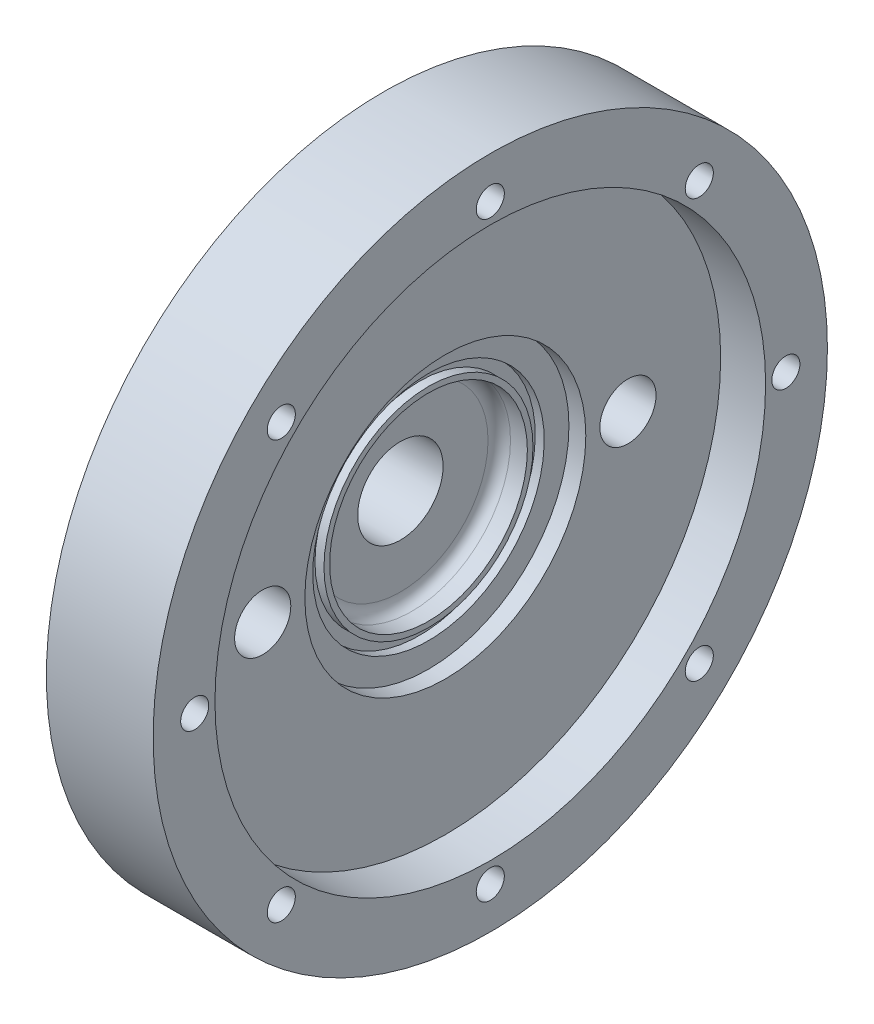
SolidWorks part; units mm, degrees
ref_plane "Front Plane" through (0, 0, 0) normal (0, 0, 1) x (1, 0, 0)
ref_plane "Top Plane" through (0, 0, 0) normal (0, 1, 0) x (1, 0, 0)
ref_plane "Right Plane" through (0, 0, 0) normal (1, 0, 0) x (0, 0, -1)
sketch "Sketch1" plane through (0, 0, 0) normal (0, 0, 1) x (1, 0, 0)
  line L1 (0, 76.2) -> (-10.16, 76.2)
  line L2 (-10.16, 76.2) -> (-10.16, 21.082)
  line L3 (-15.24, 16.002) -> (-31.75, 16.002)
  line L4 (-31.75, 16.002) -> (-31.75, 9.652)
  line L5 (-31.75, 9.652) -> (-6.35, 9.652)
  line L6 (-6.35, 9.652) -> (-6.35, 19.812)
  line L7 (-3.81, 22.352) -> (0, 22.352)
  line L8 (0, 22.352) -> (0, 76.2)
  line L9 (0, 0) -> (-31.75, 0) construction
  line L10 (-31.75, 0) -> (-31.75, 9.652) construction
  arc A0 (-10.16, 21.082) -> (-15.24, 16.002) centre (-15.24, 21.082) cw
  arc A2 (-6.35, 19.812) -> (-3.81, 22.352) centre (-3.81, 19.812) cw
  dimension "Top Part Outer Fillet" = 5.08
  dimension "LOX Manifold Fillet" = 2.54
  dimension "LOX Valve Thickness" = 6.35
  dimension "Distance between Manifold and Outer Surface" = 3.81
  dimension "LOX Valve Radius" = 9.652
  dimension "Depth of LOX Manifold" = 6.35
  dimension "Valve Entry Depth" = 25.4
  dimension "Comp Radius" = 76.2
  dimension "Manifold Radius" = 22.352
revolve "Revolve1" add sketch "Sketch1" angle 360 about L9
sketch "Sketch4" plane through (0, 0, 0) normal (0, 0, 1) x (1, 0, 0)
  line L0 (0, -76.2) -> (0, 76.2) construction
  line L1 (0, 23.622) -> (-2.032, 23.622)
  line L2 (0, 23.622) -> (0, 26.162)
  line L3 (0, 26.162) -> (-2.032, 26.162)
  line L4 (-2.032, 23.622) -> (-2.032, 26.162)
  line L5 (0, 0) -> (-31.75, 0) construction
  line L6 (-31.75, 16.002) -> (-31.75, -16.002) construction
  dimension "Top ORing Width" = 2.54
  dimension "Top ORing Depth" = 2.032
  dimension "Top ORing Radius" = 23.622
revolve "Cut-Revolve1" cut sketch "Sketch4" angle 360 about L5
sketch "Sketch5" plane through (0, 0, 0) normal (1, 0, 0) x (0, 0, -1)
  circle A0 centre (0, 0) radius 31.75
  circle A1 centre (0, 0) radius 76.2
extrude "Boss-Extrude1" add sketch "Sketch5" along normal blind 3.81
sketch "Sketch6" plane through (3.81, 0, 0) normal (1, 0, 0) x (0, 0, -1)
  circle A0 centre (0, 0) radius 62.23
  circle A1 centre (0, 0) radius 76.2
extrude "Boss-Extrude2" add sketch "Sketch6" along normal blind 10.16
sketch "Sketch2" plane through (0, 0, 0) normal (1, 0, 0) x (0, 0, -1)
  line L0 (-41.275, 0) -> (41.275, 0) construction
  circle A0 centre (41.275, 0) radius 6.35
  circle A1 centre (-41.275, 0) radius 6.35
  point P8 (0, 0)
  dimension "Valve Diameter" = 12.7
  dimension "Distance of Prop Valves" = 82.55
extrude "Cut-Extrude1" cut sketch "Sketch2" against normal through all and the other way through all
sketch "Sketch3" plane through (0, 0, 0) normal (1, 0, 0) x (0, 0, -1)
  line L0 (0, 0) -> (66.802, 0) construction
  circle A0 centre (66.802, 0) radius 3.175
  dimension "Screw Hole Diameter" = 6.35
  dimension "Distance of Screw Holes from Center" = 66.802
extrude "Cut-Extrude2" cut sketch "Sketch3" against normal through all both and the other way through all
pattern_circular "CirPattern1" count 8 over 360 about axis through (0, 0, 0) along (1, 0, 0) of "Cut-Extrude2"
